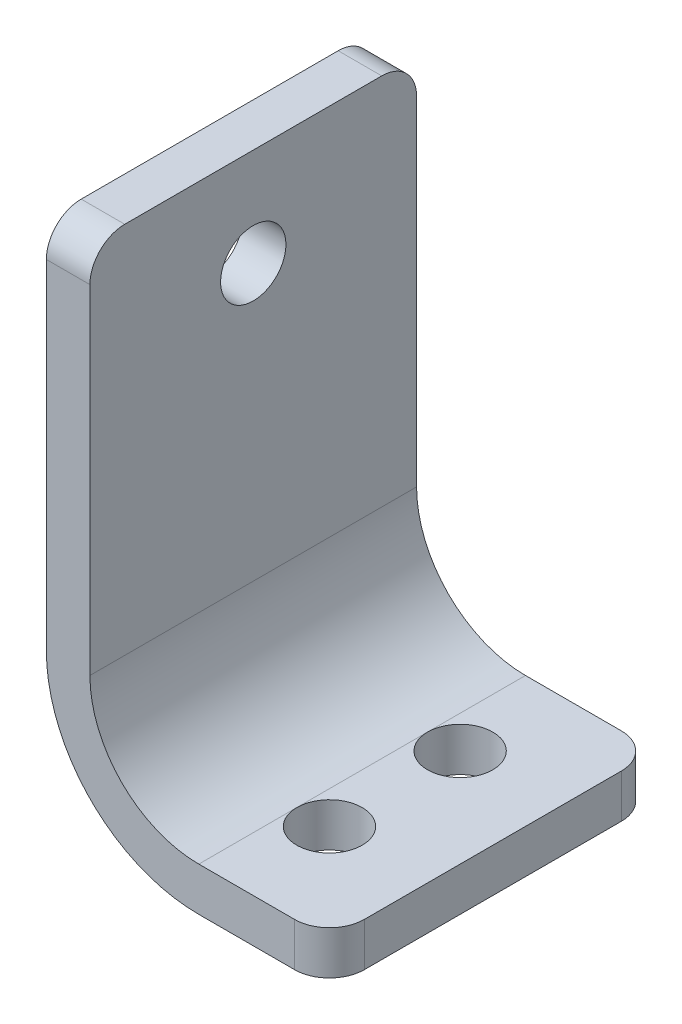
SolidWorks part; units mm, degrees
material "6061 Alloy"
ref_plane "Front Plane" through (0, 0, 0) normal (0, 0, 1) x (1, 0, 0)
ref_plane "Top Plane" through (0, 0, 0) normal (0, 1, 0) x (1, 0, 0)
ref_plane "Right Plane" through (0, 0, 0) normal (1, 0, 0) x (0, 0, -1)
sketch "Sketch1" plane through (0, 0, 0) normal (0, 0, 1) x (1, 0, 0)
  line L0 (0, 19.9955) -> (0, -7.2191)
  line L1 (7.9375, -15.1566) -> (17.4625, -15.1566)
  line L2 (-3.175, 19.9955) -> (-3.175, -7.2191)
  line L3 (7.9375, -18.3316) -> (17.4625, -18.3316)
  line L4 (0, 19.9955) -> (-3.175, 19.9955)
  line L5 (17.4625, -15.1566) -> (17.4625, -18.3316)
  arc A0 (7.9375, -15.1566) -> (0, -7.2191) centre (7.9375, -7.2191) cw
  arc A1 (7.9375, -18.3316) -> (-3.175, -7.2191) centre (7.9375, -7.2191) cw
  dimension "D1" = 7.9375
  dimension "D3" = 9.525
  dimension "D4" = 38.3271
  dimension "D2" = 3.175
extrude "Boss-Extrude1" add sketch "Sketch1" along normal blind 23.8125
sketch "Sketch5" plane through (-3.175, 0, 0) normal (-1, 0, 0) x (0, 0, 1)
  line L0 (11.9062, 15.233) -> (11.9063, 19.9955) construction
  line L1 (11.9062, 15.233) -> (11.9062, 12.8517) construction
  line L4 (23.8125, 19.9955) -> (0, 19.9955)
  line L5 (0, 19.9955) -> (0, -7.2191)
  line L6 (0, -7.2191) -> (23.8125, -7.2191)
  line L7 (23.8125, -7.2191) -> (23.8125, 19.9955)
  line L8 (23.8125, 19.9955) -> (0, 19.9955)
  line L9 (0, 19.9955) -> (0, -7.2191)
  line L10 (0, -7.2191) -> (23.8125, -7.2191)
  line L11 (23.8125, -7.2191) -> (23.8125, 19.9955)
  circle A6 centre (11.9062, 12.8517) radius 2.3813
  dimension "D2" = 4.7625
  dimension "D3" = 4.7625
  dimension "D1" = 0
extrude "Cut-Extrude2" cut sketch "Sketch5" against normal up to next (3.175 mm away) from surface at 0 contours A6 starting at face at (-3.175, 6.3882, 11.9062)
sketch "Sketch8" plane through (0, -15.1566, 0) normal (0, 1, 0) x (1, 0, 0)
  line L0 (17.4625, -23.8125) -> (7.9375, -23.8125) construction
  line L1 (17.4625, 0) -> (7.9375, 0) construction
  line L5 (7.9375, -23.8125) -> (7.9375, 0) construction
  circle A0 centre (10.3187, -7.1438) radius 2.3813
  circle A1 centre (10.3187, -16.6687) radius 2.3813
  point P2 (10.3187, -4.7625)
  point P5 (10.3187, -19.05)
  dimension "D1" = 4.7625
  dimension "D2" = 4.7625
  dimension "D3" = 4.7625
  dimension "D4" = 4.7625
extrude "Cut-Extrude3" cut sketch "Sketch8" against normal up to next
fillet "Fillet1" radius 2.54 4 edges at (17.4625, -16.7441, 0) (17.4625, -16.7441, 23.8125) (-1.5875, 19.9955, 0) (-1.5875, 19.9955, 23.8125)
sketch "Sketch2" plane through (-3.175, 0, 0) normal (-1, 0, 0) x (0, 0, 1)
  line L0 (21.2725, 19.9955) -> (2.54, 19.9955) construction
  line L1 (21.2725, 19.9955) -> (2.54, 19.9955) construction
  line L6 (9.2563, 13.9764) -> (9.9092, 2.0264)
  line L7 (14.5563, 13.9764) -> (13.9033, 2.0264)
  circle A0 centre (11.9063, 16.1855) radius 1.143
  arc A6 (14.5563, 13.9764) -> (9.2563, 13.9764) centre (11.9063, 16.1855) ccw
  arc A7 (9.9092, 2.0264) -> (13.9033, 2.0264) centre (11.9062, 2.1355) ccw
  circle A11 centre (11.9062, 1.7355) radius 0.6
  circle A15 centre (11.9063, 5.7355) radius 0.6
  circle A17 centre (11.9062, 9.7355) radius 0.6
  point P13 (11.9062, 19.9955)
  dimension "D1" = 6.9
  dimension "D2" = 4
  dimension "D7" = 1.2
  dimension "D8" = 6.45
  dimension "D10" = 2.286
  dimension "D3" = 11.95
  dimension "D4" = 0.653
  dimension "D5" = 5.3
  dimension "D6" = 3.994
  dimension "D9" = 4
  dimension "D11" = 4
  dimension "D12" = 3.81
sketch "Sketch3" plane through (-3.175, 0, 0) normal (-1, 0, 0) x (0, 0, 1)
  line L0 (11.9062, 19.9955) -> (11.9063, -7.2191)
  line L1 (21.2725, 19.9955) -> (2.54, 19.9955) construction
  line L2 (23.8125, -7.2191) -> (0, -7.2191) construction
sketch "Sketch9" plane through (0, -18.3316, 0) normal (0, -1, 0) x (1, 0, 0)
  line L0 (17.4625, 11.9062) -> (7.9375, 11.9062) construction
  line L1 (17.4625, 21.2725) -> (17.4625, 2.54) construction
  line L2 (7.9375, 16.6687) -> (7.9375, 7.1438) construction
  point P2 (0, 0)
  point P6 (17.4625, 11.9062)
  point P7 (7.9375, 11.9062)
